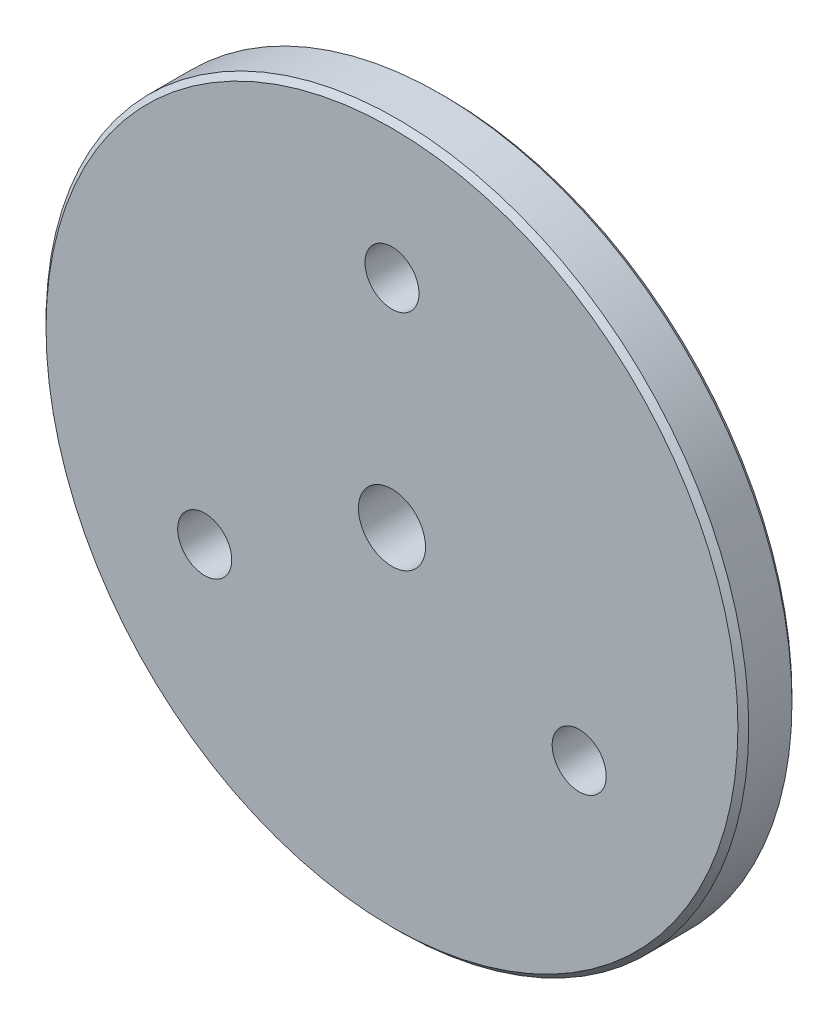
SolidWorks part; units mm, degrees
ref_plane "Front Plane" through (0, 0, 0) normal (0, 0, 1) x (1, 0, 0)
ref_plane "Top Plane" through (0, 0, 0) normal (0, 1, 0) x (1, 0, 0)
ref_plane "Right Plane" through (0, 0, 0) normal (1, 0, 0) x (0, 0, -1)
sketch "Sketch1" plane through (0, 0, 0) normal (0, 0, 1) x (1, 0, 0)
  line L0 (0, 0) -> (0, 20) construction
  line L1 (0, 0) -> (17.3205, -10) construction
  line L2 (0, 0) -> (-17.3205, -10) construction
  circle A0 centre (0, 0) radius 32.5
  circle A1 centre (0, 20) radius 2.5
  circle A2 centre (-17.3205, -10) radius 2.5
  circle A3 centre (17.3205, -10) radius 2.5
  dimension "D1" = 65
  dimension "D3" = 5
  dimension "D4" = 5
  dimension "D5" = 5
  dimension "D2" = 20
  dimension "D6" = 120
  dimension "D7" = 120
extrude "Boss-Extrude1" add sketch "Sketch1" along normal blind 5
sketch "Sketch2" plane through (0, 0, 0) normal (0, 0, -1) x (-1, 0, 0)
  circle A0 centre (0, 0) radius 10
  dimension "D1" = 20
extrude "Boss-Extrude2" add sketch "Sketch2" along normal blind 14.5
sketch "Sketch3" plane through (0, 0, -14.5) normal (0, 0, -1) x (-1, 0, 0)
  circle A0 centre (0, 0) radius 3.1
  dimension "D1" = 6.2
extrude "Cut-Extrude1" cut sketch "Sketch3" against normal blind 24.5
sketch "Sketch7" plane through (0, 0, -14.5) normal (0, 0, -1) x (-1, 0, 0)
  line L0 (0, 0) -> (0, 2.5) construction
  line L1 (0, 2.5) -> (-9.6825, 2.5) construction
  line L2 (0, 2.5) -> (9.6825, 2.5) construction
  line L3 (0, 2.5) -> (0, 6.5) construction
  line L4 (0, 6.5) -> (-7.5993, 6.5)
  line L5 (0, 6.5) -> (7.5993, 6.5)
  circle A0 centre (0, 0) radius 10 construction
  circle A1 centre (0, 0) radius 10 construction
  arc A2 (-7.5993, 6.5) -> (7.5993, 6.5) centre (0, 0) cw
  dimension "D1" = 2.5
  dimension "D2" = 4
extrude "Cut-Extrude3" cut sketch "Sketch7" against normal blind 14.5
sketch "Sketch8" plane through (0, 6.5, 0) normal (0, 1, 0) x (1, 0, 0)
  line L0 (-7.5993, 14.5) -> (7.5993, 14.5) construction
  line L1 (7.5993, 14.5) -> (-7.5993, 14.5) construction
  line L2 (10, 14.5) -> (-10, 14.5) construction
  line L3 (7.5993, 14.5) -> (0, 14.5) construction
  line L4 (0, 14.5) -> (0, 0) construction
  circle A0 centre (0, 7.25) radius 1.5
  dimension "D1" = 3
extrude "Cut-Extrude5" cut sketch "Sketch8" against normal blind 5
chamfer "Chamfer2" distance 0.5 angle 45 4 edges at (0, -10, 0) (0, -10, -14.5) (32.5, 0, 0) (32.5, 0, 5)
